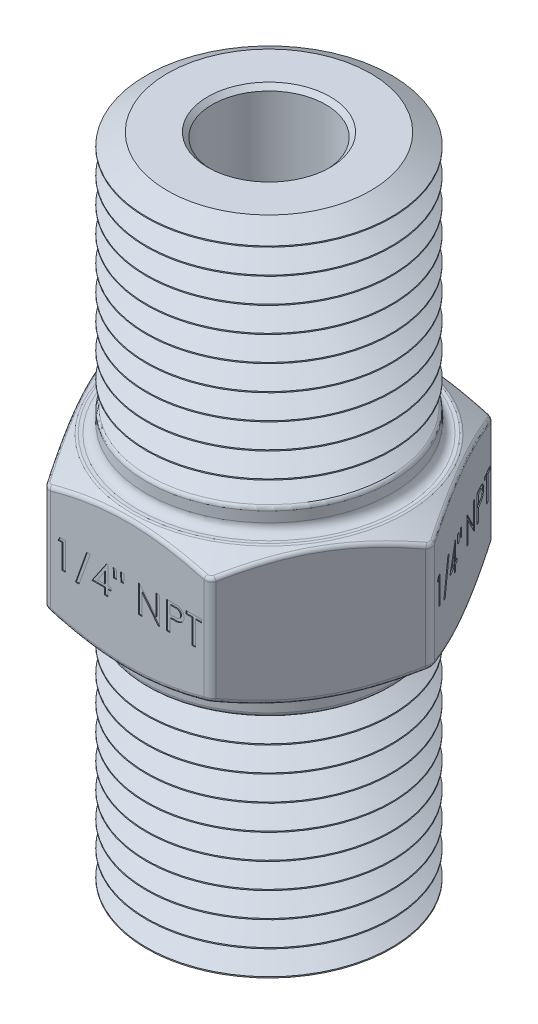
SolidWorks part; units mm, degrees
material "Plain Carbon Steel"
ref_plane "Front Plane" through (0, 0, 0) normal (0, 0, 1) x (1, 0, 0)
ref_plane "Top Plane" through (0, 0, 0) normal (0, 1, 0) x (1, 0, 0)
ref_plane "Right Plane" through (0, 0, 0) normal (1, 0, 0) x (0, 0, -1)
sketch "Sketch1" plane through (0, 0, 0) normal (0, 1, 0) x (1, 0, 0)
  line L1 (9.1654, 0) -> (4.5827, 7.9375)
  line L2 (4.5827, 7.9375) -> (-4.5827, 7.9375)
  line L3 (-4.5827, 7.9375) -> (-9.1654, 0)
  line L4 (-9.1654, 0) -> (-4.5827, -7.9375)
  line L5 (-4.5827, -7.9375) -> (4.5827, -7.9375)
  line L6 (4.5827, -7.9375) -> (9.1654, 0)
  circle A0 centre (0, 0) radius 7.9375 construction
  dimension "D1" = 15.875
extrude "Boss-Extrude1" add sketch "Sketch1" along normal mid plane 7.62
sketch "Sketch2" plane through (0, 0, 0) normal (0, 1, 0) x (1, 0, 0)
  circle A0 centre (0, 0) radius 6.858
  dimension "D1" = 13.716
extrude "Boss-Extrude2" add sketch "Sketch2" along normal mid plane 36.83
sketch "Sketch3" plane through (0, 0, 0) normal (0, 0, 1) x (1, 0, 0)
  line L0 (0, 0) -> (0, 18.415) construction
  line L1 (6.858, 18.415) -> (-6.858, 18.415) construction
  line L2 (0, 18.415) -> (5.6896, 18.415) construction
  line L3 (5.6896, 18.415) -> (6.9117, 18.415) construction
  line L4 (6.9117, 18.415) -> (8.3228, 18.415) construction
  line L5 (8.3228, 19.1206) -> (8.3228, 17.7094)
  line L6 (6.9117, 19.1206) -> (6.9117, 17.7094) construction
  line L7 (8.3228, 19.1206) -> (6.9117, 19.1206)
  line L8 (6.9117, 19.1206) -> (5.6896, 18.415)
  line L9 (5.6896, 18.415) -> (6.9117, 17.7094)
  line L10 (6.9117, 17.7094) -> (8.3228, 17.7094)
  dimension "D1" = 60
  dimension "D2" = 1.4111
  dimension "D3" = 5.6896
revolve "Cut-Revolve1" cut sketch "Sketch3" angle 360 about L0
pattern_linear "LPattern1" count 10 spacing 1.4111 along (0, -1, 0) of "Cut-Revolve1"
mirror "Mirror1" about plane through (0, 0, 0) normal (0, 1, 0) of "LPattern1", "Cut-Revolve1"
sketch "Sketch4" plane through (0, 18.415, 0) normal (0, 1, 0) x (1, 0, 0)
  circle A0 centre (0, 0) radius 3.175
  dimension "D1" = 6.35
extrude "Cut-Extrude1" cut sketch "Sketch4" against normal up to surface (36.83 mm away) up to face at (0, -18.415, -5.6896)
sketch "Sketch5" plane through (0, 0, 0) normal (0, 0, 1) x (1, 0, 0)
  line L0 (0, 3.81) -> (0, -3.81) construction
  line L1 (-4.5827, 3.81) -> (4.5827, 3.81) construction
  line L2 (0, 3.81) -> (7.62, 3.81) construction
  line L3 (4.5827, 3.81) -> (9.1654, 3.81) construction
  line L4 (7.62, 3.81) -> (7.62, -3.81) construction
  line L5 (4.5827, -3.81) -> (9.1654, -3.81) construction
  line L6 (7.62, -3.81) -> (0, -3.81) construction
  line L7 (7.62, 3.81) -> (9.1654, 3.81)
  line L8 (9.1654, 3.81) -> (9.1654, 2.9177)
  line L9 (9.1654, 3.81) -> (9.1654, -3.81) construction
  line L10 (9.1654, 2.9177) -> (7.62, 3.81)
  line L11 (7.62, -3.81) -> (9.1654, -3.81)
  line L12 (9.1654, -3.81) -> (9.1654, -2.9177)
  line L13 (9.1654, -2.9177) -> (7.62, -3.81)
  dimension "D1" = 30
  dimension "D2" = 7.62
revolve "Cut-Revolve2" cut sketch "Sketch5" angle 360 about L0
fillet "Fillet1" radius 0.508 2 edges at (0, -3.81, 6.858) (0, 3.81, 6.858)
fillet "Fillet2" radius 0.508 6 edges at (9.1654, 0, 0) (4.5827, 0, 7.9375) (-4.5827, 0, 7.9375) (-9.1654, 0, 0) (-4.5827, 0, -7.9375) (4.5827, 0, -7.9375)
fillet "Fillet3" radius 0.254 28 edges at (4.5799, -2.9641, -7.8463) (-4.5051, -2.9641, -7.8894) (-6.7111, -3.6228, -4.251) (-9.085, -2.9641, -0.0431) (-7.037, -3.6228, 3.6865) (-4.5799, -2.9641, 7.8463) (4.5051, -2.9641, 7.8894) (6.7111, -3.6228, 4.251) (9.085, -2.9641, 0.0431) (7.037, -3.6228, -3.6865) (0, -3.81, 7.62) (4.5799, 2.9641, 7.8463) (-4.5051, 2.9641, 7.8894) (-6.7111, 3.6228, 4.251) (-9.085, 2.9641, 0.0431) (-7.037, 3.6228, -3.6865) (-4.5799, 2.9641, -7.8463) (4.5051, 2.9641, -7.8894) (6.7111, 3.6228, -4.251) (9.085, 2.9641, -0.0431) (7.037, 3.6228, 3.6865) (0, 3.81, 7.62) (0, 5.0404, -6.858) (0, -5.0404, 6.858)
sketch "Sketch6" plane through (0, 0, 7.9375) normal (0, 0, 1) x (1, 0, 0)
  line L0 (0, 0) -> (0, -0.6802) construction
  line L1 (-4.2894, -0.6802) -> (4.2894, -0.6802) construction
  line L2 (4.2894, -2.8356) -> (4.2894, 2.8356) construction
  text T0 "1/4\" NPT" font "Century Gothic" height 1.524
extrude "Cut-Extrude2" cut sketch "Sketch6" against normal blind 0.0508
pattern_circular "CirPattern1" count 3 over 360 about axis through (0, 18.415, 0) along (0, -1, 0) of "Cut-Extrude2"
chamfer "Chamfer1" distance 0.254 angle 45 2 edges at (0, -18.415, 3.175) (0, 18.415, 3.175)
